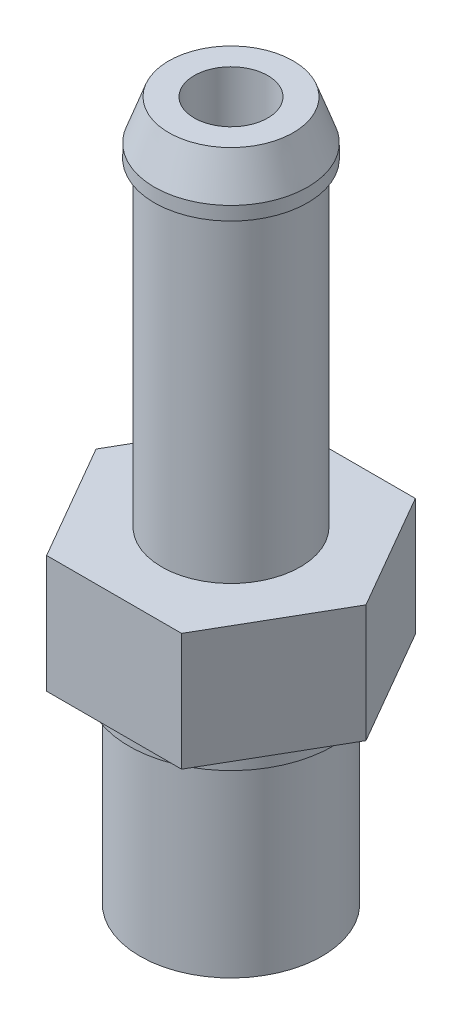
SolidWorks part; units mm, degrees
material "1060 Alloy"
ref_plane "Front Plane" through (0, 0, 0) normal (0, 0, 1) x (1, 0, 0)
ref_plane "Top Plane" through (0, 0, 0) normal (0, 1, 0) x (1, 0, 0)
ref_plane "Right Plane" through (0, 0, 0) normal (1, 0, 0) x (0, 0, -1)
sketch "Sketch1" plane through (0, 0, 0) normal (0, 1, 0) x (1, 0, 0)
  line L1 (9.2241, 0) -> (4.612, 7.9883)
  line L2 (4.612, 7.9883) -> (-4.612, 7.9883)
  line L3 (-4.612, 7.9883) -> (-9.2241, 0)
  line L4 (-9.2241, 0) -> (-4.612, -7.9883)
  line L5 (-4.612, -7.9883) -> (4.612, -7.9883)
  line L6 (4.612, -7.9883) -> (9.2241, 0)
  circle A0 centre (0, 0) radius 7.9883 construction
  dimension "D1" = 15.9766
extrude "Boss-Extrude1" add sketch "Sketch1" along normal blind 8.0391
sketch "Sketch3" plane through (0, 8.0391, 0) normal (0, 1, 0) x (1, 0, 0)
  circle A0 centre (0, 0) radius 4.7371
  dimension "D1" = 9.4742
extrude "Boss-Extrude2" add sketch "Sketch3" along normal blind 21.8059
sketch "Sketch4" plane through (0, 29.845, 0) normal (0, 1, 0) x (1, 0, 0)
  circle A0 centre (0, 0) radius 5.2387
  dimension "D1" = 10.4775
extrude "Boss-Extrude3" add sketch "Sketch4" along normal blind 0.9271
ref_plane "Plane1" through (0, 33.5026, 0) normal (0, 1, 0) x (1, 0, 0)
sketch "Sketch5" plane through (0, 33.5026, 0) normal (0, 1, 0) x (1, 0, 0)
  circle A0 centre (0, 0) radius 4.2545
  circle A1 centre (0, 0) radius 2.4956
  dimension "D1" = 8.509
  dimension "D2" = 4.9911
sketch "Sketch9" plane through (0, 30.7721, 0) normal (0, 1, 0) x (1, 0, 0)
  circle A0 centre (0, 0) radius 5.2387
sketch "Sketch10" plane through (0, 0, 0) normal (1, 0, 0) x (0, 0, -1)
  line L0 (0, 33.5026) -> (-2.4955, 33.5026)
  line L1 (4.2545, 33.5026) -> (-4.2545, 33.5026) construction
  line L2 (5.7626, 33.5026) -> (-5.7626, 33.5026) construction
  line L3 (0, 33.5026) -> (-4.2545, 33.5026)
  line L4 (-4.2545, 33.5026) -> (-5.2387, 30.7721)
  line L5 (-5.2387, 30.7721) -> (0, 30.7721)
  line L6 (0, 30.7721) -> (0, 33.5026)
  line L7 (-2.4955, 33.5026) -> (-4.2545, 33.5026)
  dimension "D1" = 2.4956
  dimension "D2" = 4.2545
revolve "Revolve1" add sketch "Sketch10" angle 360 about L6
sketch "Sketch11" plane through (0, 0, 0) normal (0, -1, 0) x (-1, 0, 0)
  circle A0 centre (0, 0) radius 6.9659
  dimension "D1" = 13.9319
extrude "Boss-Extrude4" add sketch "Sketch11" along normal blind 1.4605
sketch "Sketch12" plane through (0, -1.4605, 0) normal (0, -1, 0) x (-1, 0, 0)
  circle A0 centre (0, 0) radius 6.223
  dimension "D1" = 12.446
extrude "Boss-Extrude5" add sketch "Sketch12" along normal blind 12.8016
thread "Thread1" pitch 1.27 start angle 0, offset 0, length 0, pitch 1.27, diameter 12.446
ref_plane "Plane2" through (6.223, -14.2621, 0) normal (0, 0, 1) x (1, 0, 0)
sketch "Thread Profile1" plane through (6.223, -14.2621, 0) normal (0, 0, 1) x (1, 0, 0)
  line L0 (0, 0) -> (0, 1.27) construction
  line L1 (0, 0) -> (0.6874, 0.3969)
  line L2 (0.6874, 0.3969) -> (0.6874, 0.5556)
  line L3 (0.6874, 0.5556) -> (0, 0.9525)
  line L4 (0.6874, 0.4762) -> (0, 0.4762) construction
  line L11 (0, 0) -> (0, 0.9525)
  point P2 (0, 0)
  dimension "Pitch" = 1.27
  dimension "Profile_Angle" = 60
  dimension "Profile_Land" = 0.1588
  dimension "Profile_Height" = 0.6874
sketch "Sketch24" plane through (0, 33.5026, 0) normal (0, 1, 0) x (1, 0, 0)
  circle A0 centre (0, 0) radius 2.5146
  dimension "D1" = 5.0292
extrude "Cut-Extrude1" cut sketch "Sketch24" against normal through all
sketch "Sketch25" plane through (0, -14.2621, 0) normal (0, -1, 0) x (-1, 0, 0)
  circle A0 centre (0, 0) radius 3.6258
  dimension "D1" = 7.2517
extrude "Cut-Extrude2" cut sketch "Sketch25" against normal blind 16.4592
